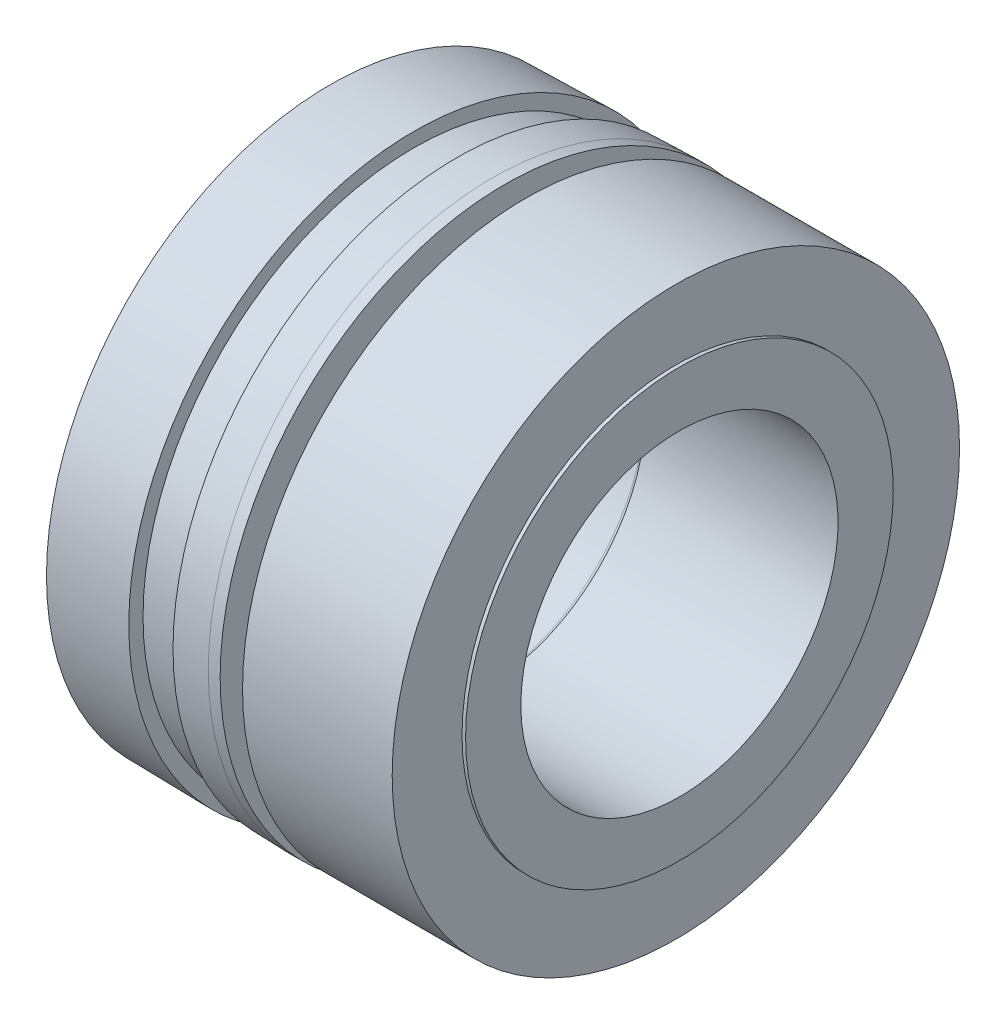
SolidWorks part; units mm, degrees
material "Alloy Steel"
ref_plane "Ön Düzlem" through (0, 0, 0) normal (0, 0, 1) x (1, 0, 0)
ref_plane "Üst Düzlem" through (0, 0, 0) normal (0, 1, 0) x (1, 0, 0)
ref_plane "Sağ Düzlem" through (0, 0, 0) normal (1, 0, 0) x (0, 0, -1)
sketch "Sketch1" plane through (0, 0, 0) normal (0, 0, 1) x (1, 0, 0)
  line L0 (-66.0265, 0) -> (62.2068, 0) construction
  line L1 (-15.3679, -22.25) -> (11.6321, -22.25)
  line L2 (-16.3633, -23.2454) -> (-21.3633, -23.2454)
  line L3 (-21.3633, -23.2454) -> (-21.3633, -30.332)
  line L4 (-24.3633, -33.332) -> (-32.9679, -33.332)
  line L5 (-34.4679, -33.332) -> (-34.4679, -34.832)
  line L6 (-34.4679, -34.832) -> (-32.9679, -34.832)
  line L7 (-32.9679, -34.832) -> (-32.9679, -33.332)
  line L8 (-34.4679, -33.332) -> (-37.3679, -33.332)
  line L9 (-25.6168, -40) -> (-37.3679, -39.7949)
  line L10 (11.6321, -30) -> (11.6321, -22.25)
  line L11 (-25.6168, -40) -> (-25.6168, -38)
  line L12 (-37.3679, -33.332) -> (-37.3679, -39.7949)
  line L13 (-25.6168, -38) -> (-19.6168, -38)
  line L14 (-19.6168, -38) -> (-19.6168, -39.7949)
  line L15 (-12.8633, -39.9365) -> (-12.8633, -35)
  line L16 (-12.8633, -35) -> (-9.8633, -35)
  line L17 (-9.8633, -35) -> (-9.8633, -39.7949)
  line L18 (-19.6168, -39.7949) -> (-14.5313, -39.9365)
  line L19 (-9.8633, -39.7949) -> (11.1321, -39.7949)
  line L20 (-14.5313, -39.9365) -> (-12.8633, -39.9365)
  line L21 (11.1321, -39.7949) -> (11.1321, -30)
  line L22 (11.1321, -30) -> (11.6321, -30)
  arc A0 (-15.3679, -22.25) -> (-16.3633, -23.2454) centre (-16.3633, -22.25) cw
  arc A1 (-21.3633, -30.332) -> (-24.3633, -33.332) centre (-24.3633, -30.332) cw
  dimension "D3" = 5
  dimension "D4" = 49
  dimension "D1" = 22.25
  dimension "D2" = 27
  dimension "D5" = 1.5
  dimension "D6" = 1.5
  dimension "D7" = 2
  dimension "D8" = 6
  dimension "D9" = 4.9365
  dimension "D10" = 0.5
  dimension "D11" = 3
  dimension "D12" = 30
revolve "Revolve1" add sketch "Sketch1" angle 360 about L0
cosmetic thread "Cosmetic Thread1"
